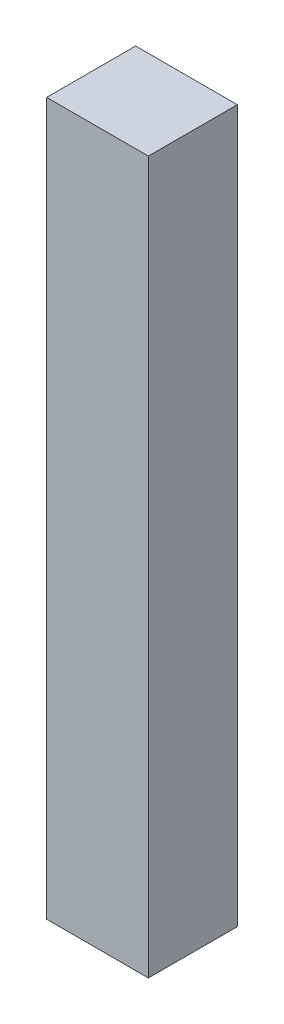
SolidWorks part; units mm, degrees
ref_plane "Front Plane" through (0, 0, 0) normal (0, 0, 1) x (1, 0, 0)
ref_plane "Top Plane" through (0, 0, 0) normal (0, 1, 0) x (1, 0, 0)
ref_plane "Right Plane" through (0, 0, 0) normal (1, 0, 0) x (0, 0, -1)
sketch "Sketch2" plane through (0, 0, 0) normal (0, 1, 0) x (1, 0, 0)
  line L0 (-4.6922, 0) -> (4.3541, 0) construction
  line L2 (-4, 3.5) -> (4, 3.5)
  line L3 (-4, 3.5) -> (-4, -3.5)
  line L4 (-4, -3.5) -> (4, -3.5)
  line L5 (4, 3.5) -> (4, -3.5)
  line L6 (-4, 3.5) -> (4, -3.5) construction
  line L7 (-4, -3.5) -> (4, 3.5) construction
  point P3 (0, 0)
  dimension "D1" = 8
  dimension "D2" = 7
extrude "Boss-Extrude1" add sketch "Sketch2" along normal mid plane 56
